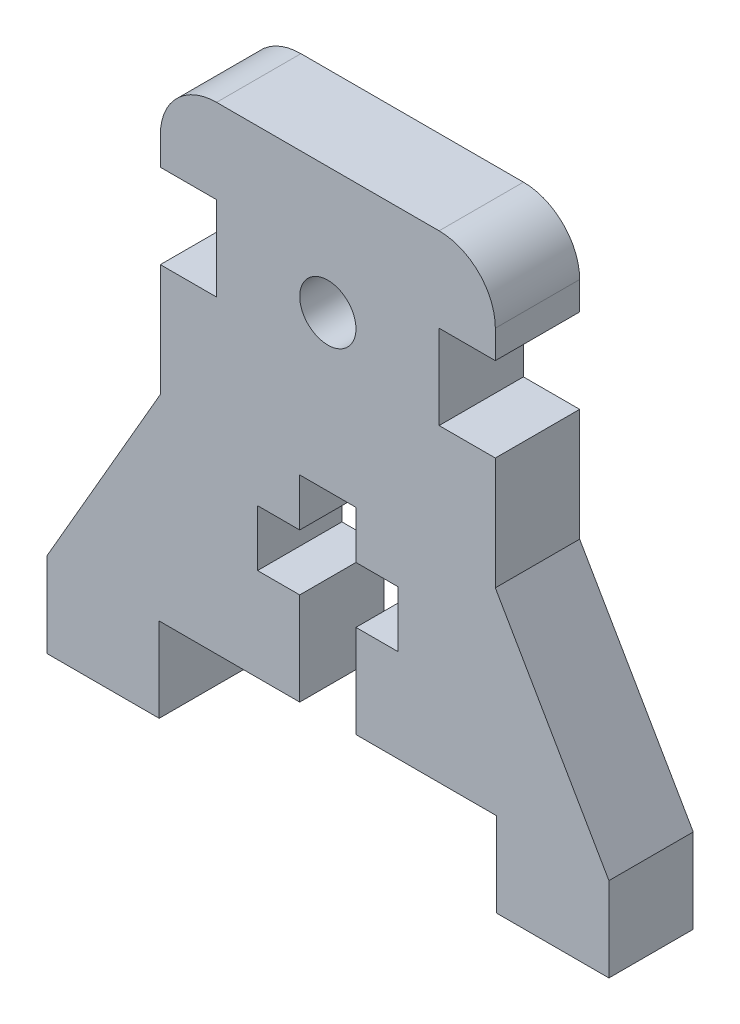
SolidWorks part; units mm, degrees
ref_plane "Plan de face" through (0, 0, 0) normal (0, 0, 1) x (1, 0, 0)
ref_plane "Plan de dessus" through (0, 0, 0) normal (0, 1, 0) x (1, 0, 0)
ref_plane "Plan de droite" through (0, 0, 0) normal (1, 0, 0) x (0, 0, -1)
sketch "Esquisse2" plane through (0, 0, 0) normal (0, 0, 1) x (1, 0, 0)
  line L0 (-50, 0) -> (50, 0)
  line L1 (50, 0) -> (50, 15)
  line L2 (50, 15) -> (29.7927, 50)
  line L3 (29.7927, 50) -> (29.7927, 70)
  line L4 (29.7927, 70) -> (19.7927, 70)
  line L5 (19.7927, 70) -> (19.7927, 85)
  line L6 (19.7927, 85) -> (29.7927, 85)
  line L7 (29.7927, 85) -> (29.7927, 90)
  line L8 (19.7927, 100) -> (-19.7927, 100)
  line L9 (0, 0) -> (0, 100) construction
  line L10 (-29.7927, 85) -> (-29.7927, 90)
  line L11 (-19.7927, 85) -> (-29.7927, 85)
  line L12 (-19.7927, 70) -> (-19.7927, 85)
  line L13 (-29.7927, 70) -> (-19.7927, 70)
  line L14 (-29.7927, 50) -> (-29.7927, 70)
  line L15 (-50, 15) -> (-29.7927, 50)
  line L16 (-50, 0) -> (-50, 15)
  arc A0 (29.7927, 90) -> (19.7927, 100) centre (19.7927, 90) ccw
  arc A1 (-29.7927, 90) -> (-19.7927, 100) centre (-19.7927, 90) cw
  dimension "D9" = 10
  dimension "D1" = 50
  dimension "D2" = 100
  dimension "D3" = 50
  dimension "D4" = 15
  dimension "D5" = 60
  dimension "D6" = 15
  dimension "D7" = 10
  dimension "D8" = 10
  dimension "D10" = 20
extrude "Boss.-Extru.1" add sketch "Esquisse2" along normal blind 15
sketch "Esquisse3" plane through (0, 0, 15) normal (0, 0, 1) x (1, 0, 0)
  line L0 (-50, 0) -> (50, 0) construction
  line L1 (-30, 15) -> (30, 15)
  line L2 (-30, 15) -> (-30, 0)
  line L3 (-30, 0) -> (30, 0)
  line L4 (30, 15) -> (30, 0)
  line L5 (-30, 15) -> (30, 0) construction
  line L6 (-30, 0) -> (30, 15) construction
  line L7 (50, 0) -> (50, 15) construction
  line L8 (-50, 15) -> (-50, 0) construction
  line L9 (0, 45.1548) -> (0, 0) construction
  line L10 (-5, 50) -> (5, 50)
  line L11 (-5, 50) -> (-5, 0)
  line L12 (-5, 0) -> (5, 0)
  line L13 (5, 50) -> (5, 0)
  line L14 (-5, 50) -> (5, 0) construction
  line L15 (-5, 0) -> (5, 50) construction
  line L16 (0, 100) -> (0, 45.1548) construction
  line L17 (-12.5, 41.5158) -> (12.5, 41.5158)
  line L18 (-12.5, 41.5158) -> (-12.5, 31.5158)
  line L19 (-12.5, 31.5158) -> (12.5, 31.5158)
  line L20 (12.5, 41.5158) -> (12.5, 31.5158)
  line L21 (-12.5, 41.5158) -> (12.5, 31.5158) construction
  line L22 (-12.5, 31.5158) -> (12.5, 41.5158) construction
  line L24 (19.7927, 100) -> (-19.7927, 100) construction
  line L25 (-19.7927, 77.5) -> (19.7927, 77.5) construction
  line L26 (-19.7927, 85) -> (-19.7927, 70) construction
  line L27 (19.7927, 70) -> (19.7927, 85) construction
  line L28 (-29.7927, 50) -> (29.7927, 50) construction
  circle A0 centre (0, 77.5) radius 5
  point P0 (0, 7.5)
  point P11 (0, 25)
  point P20 (0, 36.5158)
  dimension "D7" = 10
  dimension "D1" = 20
  dimension "D2" = 20
  dimension "D3" = 15
  dimension "D4" = 10
  dimension "D5" = 10
  dimension "D6" = 25
  dimension "D8" = 16.5158
extrude "Enlèv. mat.-Extru.1" cut sketch "Esquisse3" against normal blind 15 contours A0 | L11 L12 L13 L10 | L17 L20 L19 L18 | L1 L4 L3 L2
